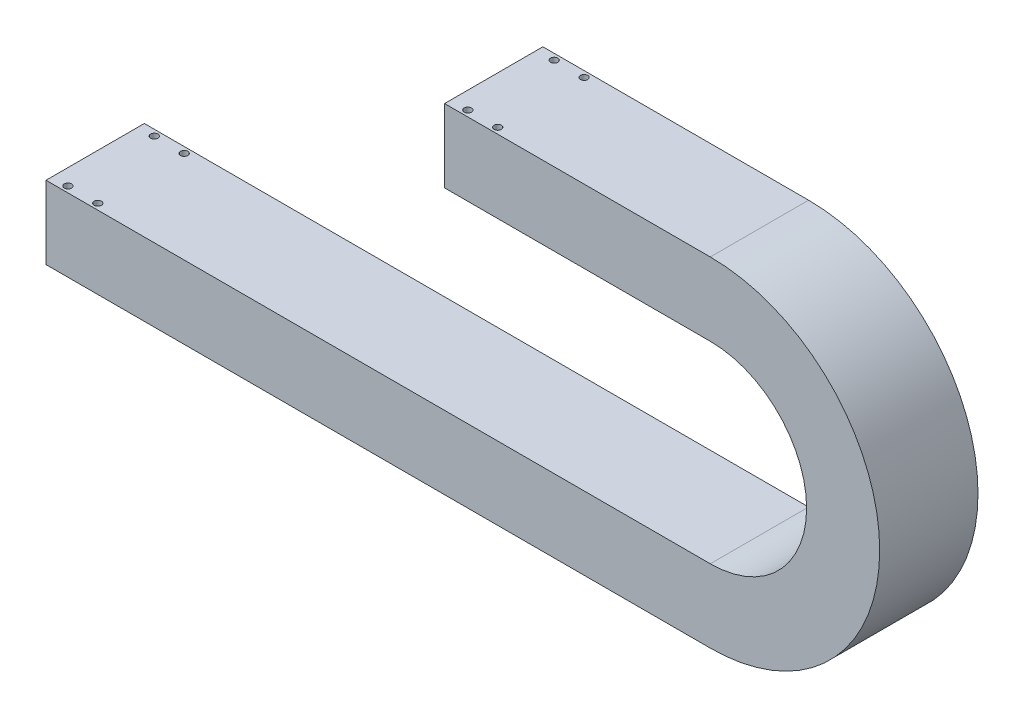
SolidWorks part; units mm, degrees
material "MC尼龙"
ref_plane "前视" through (0, 0, 0) normal (0, 0, 1) x (1, 0, 0)
ref_plane "上视" through (0, 0, 0) normal (0, 1, 0) x (1, 0, 0)
ref_plane "右视" through (0, 0, 0) normal (1, 0, 0) x (0, 0, -1)
sketch "草图1" plane through (0, 0, 0) normal (0, 0, 1) x (1, 0, 0)
  line L0 (0, 0) -> (500, 0)
  line L2 (500, 200) -> (300, 200)
  arc A0 (500, 200) -> (500, 0) centre (500, 100) cw
  dimension "D1" = 100
  dimension "D2" = 500
  dimension "D3" = 200
extrude "拉伸-薄壁1" add sketch "草图1" along normal mid plane 74 thin thin type mid plane wall 55
shell "抽壳1" thickness 12
hole_wizard "M5 间隙孔2" positions "草图3" profile "草图2" hole size "M5" standard "Gb" end condition through all
sketch "草图3" plane through (0, 27.5, 0) normal (0, 1, 0) x (1, 0, 0)
  line L0 (0, 0) -> (79.883, 0) construction
  line L1 (0, -37) -> (0, 37) construction
  point P0 (12, 32.5)
  point P2 (34.5, 32.5)
  point P9 (34.5, -32.5)
  point P10 (12, -32.5)
  dimension "D1" = 12
  dimension "D2" = 22.5
  dimension "D3" = 65
sketch "草图2" plane through (12, 27.5, -32.5) normal (1, 0, 0) x (0, 0, 1)
  line L0 (0, 0) -> (0, 55)
  line L1 (0, 55) -> (2.75, 55)
  line L2 (2.75, 55) -> (2.75, 0)
  line L5 (2.75, 0) -> (0, 0)
  line L11 (0, -6.35) -> (0, 107.95) construction
  dimension "通孔孔直径" = 5.5
  dimension "通孔孔深度" = 55
hole_wizard "M5 间隙孔1" positions "草图5" profile "草图4" hole size "M5" standard "Gb"
sketch "草图5" plane through (0, 227.5, 0) normal (0, 1, 0) x (1, 0, 0)
  line L0 (300, 0) -> (353.5459, 0) construction
  line L1 (300, -37) -> (300, 37) construction
  point P0 (313, 32.5)
  point P2 (335.5, 32.5)
  point P12 (335.5, -32.5)
  point P13 (313, -32.5)
  dimension "D1" = 13
  dimension "D2" = 22.5
sketch "草图4" plane through (313, 227.5, -32.5) normal (1, 0, 0) x (0, 0, 1)
  line L0 (0, 0) -> (0, 56.6514)
  line L1 (0, 56.6514) -> (2.75, 54.999)
  line L2 (2.75, 54.999) -> (2.75, 0)
  line L5 (2.75, 0) -> (0, 0)
  line L10 (0, 56.6514) -> (-2.75, 54.999) construction
  line L11 (0, -6.35) -> (0, 107.95) construction
  dimension "孔直径" = 5.5
  dimension "孔深度" = 54.999
  dimension "导头角度" = 118
